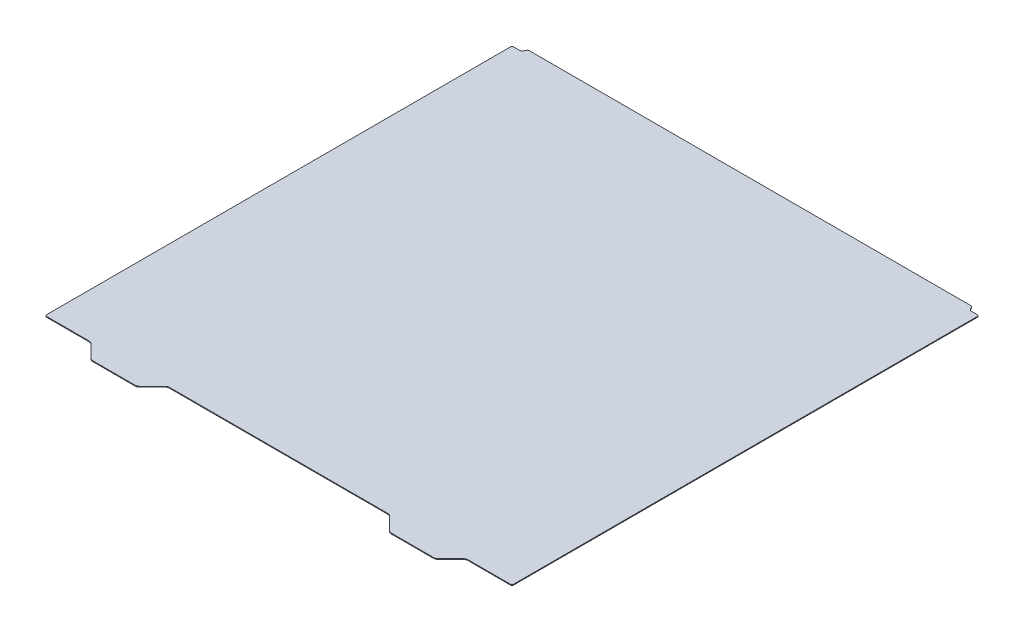
SolidWorks part; units mm, degrees
ref_plane "Front" through (0, 0, 0) normal (0, 0, 1) x (1, 0, 0)
ref_plane "Top" through (0, 0, 0) normal (0, 1, 0) x (1, 0, 0)
ref_plane "Right" through (0, 0, 0) normal (1, 0, 0) x (0, 0, -1)
sketch "Sketch1" plane through (0, 0, 0) normal (0, 1, 0) x (1, 0, 0)
  line L1 (-152.5, -152.5) -> (152.5, -152.5)
  line L2 (-152.5, -152.5) -> (-152.5, 152.5)
  line L3 (-152.5, 152.5) -> (152.5, 152.5)
  line L4 (152.5, -152.5) -> (152.5, 152.5)
  line L5 (-152.5, -152.5) -> (152.5, 152.5) construction
  line L6 (-152.5, 152.5) -> (152.5, -152.5) construction
  point P0 (0, 0)
  dimension "D1" = 305
extrude "Boss-Extrude1" add sketch "Sketch1" along normal blind 0.5
sketch "Sketch2" plane through (0, 0.5, 0) normal (0, 1, 0) x (1, 0, 0)
  line L2 (0, 155.5) -> (0, 0) construction
  line L3 (152.5, 152.5) -> (-152.5, 152.5) construction
  line L6 (-122.5, -152.5) -> (-72.5, -152.5)
  line L7 (-152.5, -152.5) -> (152.5, -152.5) construction
  line L8 (-72.5, -152.5) -> (-82.5, -162.5)
  line L9 (-82.5, -162.5) -> (-112.5, -162.5)
  line L10 (-97.5, -162.5) -> (-97.5, -152.5) construction
  line L11 (-122.5, -152.5) -> (-112.5, -162.5)
  line L12 (-72.5, -152.5) -> (-82.5, -162.5)
  line L13 (-122.5, -152.5) -> (-112.5, -162.5)
  line L14 (97.5, -162.5) -> (97.5, -152.5) construction
  line L15 (122.5, -152.5) -> (112.5, -162.5)
  line L16 (72.5, -152.5) -> (82.5, -162.5)
  line L17 (122.5, -152.5) -> (112.5, -162.5)
  line L18 (82.5, -162.5) -> (112.5, -162.5)
  line L19 (72.5, -152.5) -> (82.5, -162.5)
  line L20 (122.5, -152.5) -> (72.5, -152.5)
  line L21 (-152.5, 152.5) -> (-152.5, -152.5) construction
  line L22 (-146.634, 152.5) -> (-144.9019, 155.5)
  line L23 (-144.9019, 155.5) -> (144.9019, 155.5)
  line L24 (-146.634, 152.5) -> (146.634, 152.5)
  line L25 (146.634, 152.5) -> (144.9019, 155.5)
  point P25 (0, 152.5)
  dimension "D1" = 60
  dimension "D2" = 3
  dimension "D3" = 50
  dimension "D4" = 30
  dimension "D5" = 10
  dimension "D6" = 45
  dimension "D7" = 5.866
extrude "Boss-Extrude2" add sketch "Sketch2" against normal up to surface (0.5 mm away) up to face at (0, 0, 0)
fillet "Fillet1" radius 1 6 edges at (152.5, 0.25, 152.5) (-152.5, 0.25, 152.5) (144.9019, 0.25, -155.5) (152.5, 0.25, -152.5) (-144.9019, 0.25, -155.5) (-152.5, 0.25, -152.5)
fillet "Fillet2" radius 1.5 2 edges at (146.634, 0.25, -152.5) (-146.634, 0.25, -152.5)
fillet "Fillet3" radius 3 8 edges at (-122.5, 0.25, 152.5) (-112.5, 0.25, 162.5) (-82.5, 0.25, 162.5) (-72.5, 0.25, 152.5) (72.5, 0.25, 152.5) (82.5, 0.25, 162.5) (112.5, 0.25, 162.5) (122.5, 0.25, 152.5)
